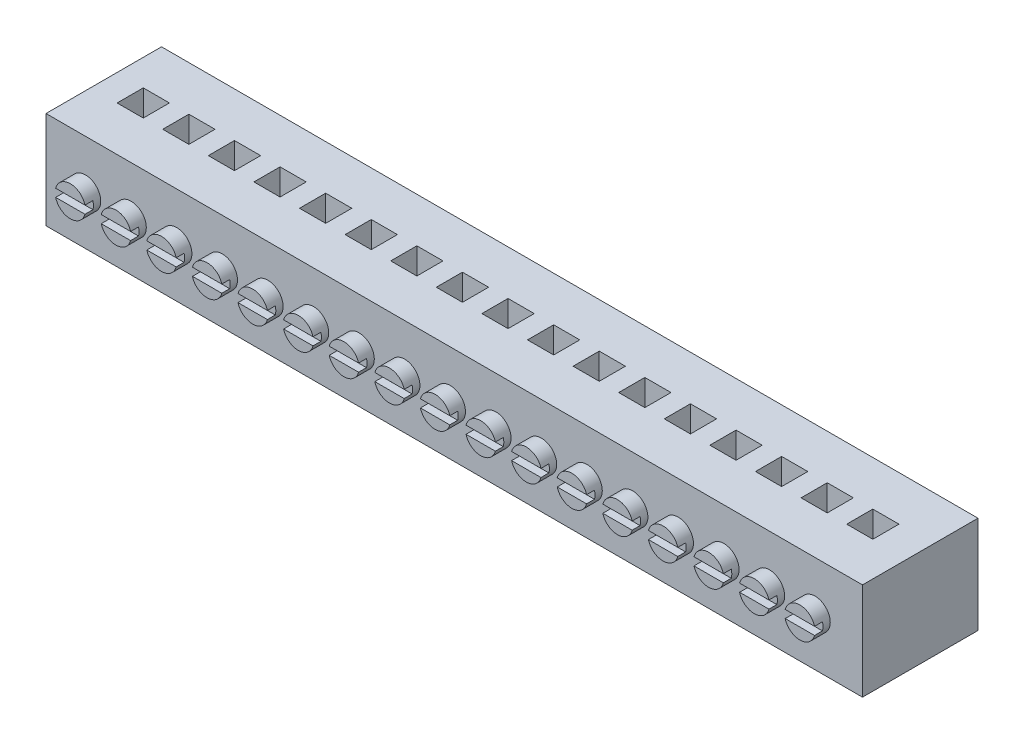
SolidWorks part; units mm, degrees
ref_plane "Front" through (0, 0, 0) normal (0, 0, 1) x (1, 0, 0)
ref_plane "Top" through (0, 0, 0) normal (0, 1, 0) x (1, 0, 0)
ref_plane "Right" through (0, 0, 0) normal (1, 0, 0) x (0, 0, -1)
sketch "Sketch1" plane through (0, 0, 0) normal (0, 0, 1) x (1, 0, 0)
  line L0 (67.15, -8) -> (-67.15, 8) construction
  line L1 (-67.15, 8) -> (67.15, 8)
  line L2 (-67.15, 8) -> (-67.15, -8)
  line L3 (-67.15, -8) -> (67.15, -8)
  line L4 (67.15, 8) -> (67.15, -8)
  dimension "D1" = 134.3
  dimension "D2" = 16
extrude "strip base" add sketch "Sketch1" along normal mid plane 19
sketch "Sketch2" plane through (0, 0, 9.5) normal (0, 0, 1) x (1, 0, 0)
  line L0 (-67.15, 0) -> (96.0532, 0) construction
  line L1 (-67.15, 8) -> (-67.15, -8) construction
  line L2 (-60.65, 0) -> (-60.65, 2.5) construction
  circle A0 centre (-60.65, 0) radius 2.5
  dimension "D2" = 5
  dimension "D1" = 6.5
extrude "screw body" add sketch "Sketch2" along normal blind 2.5
sketch "Sketch3" plane through (0, 0, 12) normal (0, 0, 1) x (1, 0, 0)
  line L0 (-58.15, 0.0032) -> (-63.15, -0.0032)
  circle A0 centre (-60.65, 0) radius 2.5 construction
  point P4 (-60.65, 0)
extrude "screw slot" cut sketch "Sketch3" against normal blind 1.3 and the other way blind 2.5 thin thin type mid plane wall 1.3
ref_plane "slot end face" through (0, 2.5, 0) normal (0, 1, 0) x (-1, 0, 0)
sketch "Sketch4" plane through (0, -8, 0) normal (0, -1, 0) x (1, 0, 0)
  line L0 (-58.5, -2.15) -> (-62.8, 2.15) construction
  line L1 (-62.8, 2.15) -> (-58.5, 2.15)
  line L2 (-62.8, 2.15) -> (-62.8, -2.15)
  line L3 (-62.8, -2.15) -> (-58.5, -2.15)
  line L4 (-58.5, 2.15) -> (-58.5, -2.15)
  line L5 (-67.15, 0) -> (88.5697, 0) construction
  line L6 (-67.15, 9.5) -> (-67.15, -9.5) construction
  line L7 (-60.65, 12) -> (-60.65, 10.7) construction
  point P4 (-60.65, 0)
  dimension "D1" = 4.3
extrude "wire hole" cut sketch "Sketch4" against normal through all
pattern_linear "LPattern1" count 17 spacing 7.5 along (1, 0, 0) of "screw body", "screw slot", "wire hole"
equation "\"D1@Sketch1\"=\"D1@LPattern1\" *7.9"
